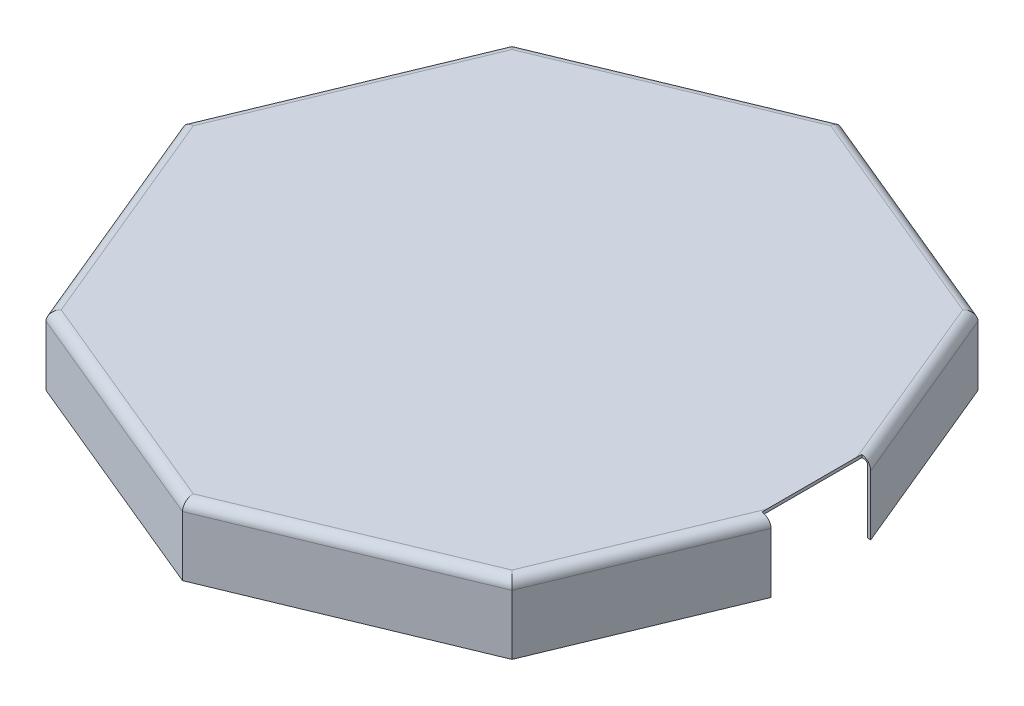
SolidWorks part; units mm, degrees
ref_plane "Front Plane" through (0, 0, 0) normal (0, 0, 1) x (1, 0, 0)
ref_plane "Top Plane" through (0, 0, 0) normal (0, 1, 0) x (1, 0, 0)
ref_plane "Right Plane" through (0, 0, 0) normal (1, 0, 0) x (0, 0, -1)
sketch "Sketch3" plane through (0, 0, 0) normal (0, 1, 0) x (1, 0, 0)
  line L0 (0, 0) -> (0, -330.5604) construction
  line L3 (0, 0) -> (0, 330.5604) construction
  line L4 (0, 0) -> (330.5604, 0) construction
  line L5 (0, 0) -> (-330.5604, 0) construction
  line L6 (0, 0) -> (233.7415, -233.7415) construction
  line L7 (0, 0) -> (233.7415, 233.7415) construction
  line L8 (0, 0) -> (-233.7415, 233.7415) construction
  line L9 (0, 0) -> (-233.7415, -233.7415) construction
  line L10 (0, 330.5604) -> (-233.7415, 233.7415)
  line L11 (-233.7415, 233.7415) -> (-330.5604, 0)
  line L12 (-330.5604, 0) -> (-233.7415, -233.7415)
  line L13 (-233.7415, -233.7415) -> (0, -330.5604)
  line L14 (0, -330.5604) -> (233.7415, -233.7415)
  line L15 (233.7415, -233.7415) -> (330.5604, 0)
  line L16 (330.5604, 0) -> (233.7415, 233.7415)
  line L17 (233.7415, 233.7415) -> (0, 330.5604)
  circle A0 centre (0, 0) radius 330.5604 construction
  dimension "D1" = 253
extrude "Boss-Extrude1" add sketch "Sketch3" along normal blind 70
shell "Shell1" thickness 3
ref_plane "Plane1" through (0, 90, 0) normal (0, 1, 0) x (1, 0, 0)
sketch "Sketch4" plane through (0, 90, 0) normal (0, 1, 0) x (1, 0, 0)
  point P0 (0, 0)
ref_plane "Plane2" through (331, 0, 0) normal (1, 0, 0) x (0, 0, -1)
sketch "Sketch5" plane through (331, 0, 0) normal (1, 0, 0) x (0, 0, -1)
  line L0 (-233.7415, 0) -> (0, 0) construction
  line L1 (-50, 0) -> (50, 0)
  line L2 (-50, 0) -> (-50, 80)
  line L3 (-50, 80) -> (50, 80)
  line L4 (50, 0) -> (50, 80)
  dimension "D1" = 100
  dimension "D2" = 50
  dimension "D3" = 80
extrude "Cut-Extrude2" cut sketch "Sketch5" against normal blind 30
fillet "Fillet1" radius 10 8 edges at (271.7956, 70, 141.8708) (116.8708, 70, 282.151) (-116.8708, 70, 282.151) (-282.151, 70, 116.8708) (-282.151, 70, -116.8708) (-116.8708, 70, -282.151) (116.8708, 70, -282.151) (271.7956, 70, -141.8708)
fillet "Fillet2" radius 3 8 edges at (269.024, 67, -140.7227) (269.024, 67, 140.7227) (115.7227, 67, 279.3793) (-115.7227, 67, 279.3793) (-279.3793, 67, 115.7227) (-279.3793, 67, -115.7227) (-115.7227, 67, -279.3793) (115.7227, 67, -279.3793)
